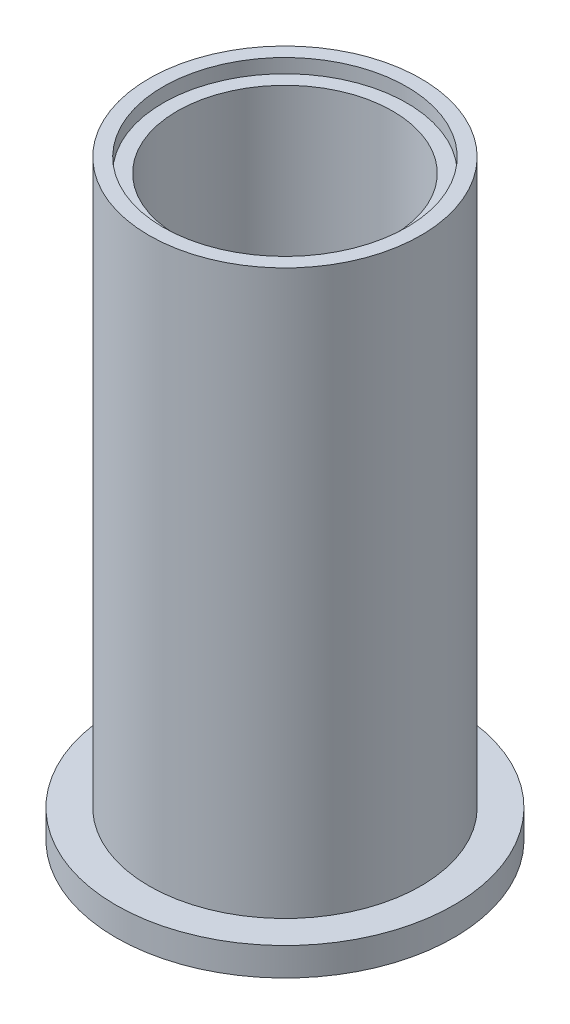
SolidWorks part; units mm, degrees
ref_plane "Front Plane" through (0, 0, 0) normal (0, 0, 1) x (1, 0, 0)
ref_plane "Top Plane" through (0, 0, 0) normal (0, 1, 0) x (1, 0, 0)
ref_plane "Right Plane" through (0, 0, 0) normal (1, 0, 0) x (0, 0, -1)
sketch "Sketch1" plane through (0, 0, 0) normal (0, 1, 0) x (1, 0, 0)
  circle A0 centre (0, 0) radius 60
  dimension "D1" = 120
extrude "Boss-Extrude1" add sketch "Sketch1" along normal blind 10
sketch "Sketch2" plane through (0, 10, 0) normal (0, 1, 0) x (1, 0, 0)
  circle A0 centre (0, 0) radius 38.25
  circle A1 centre (0, 0) radius 48.25
  dimension "D1" = 10
  dimension "D2" = 96.5
extrude "Boss-Extrude2" add sketch "Sketch2" along normal blind 200
sketch "Sketch3" plane through (0, 210, 0) normal (0, 1, 0) x (1, 0, 0)
  circle A0 centre (0, 0) radius 43.25
  circle A1 centre (0, 0) radius 38.25 construction
  dimension "D1" = 5
extrude "Cut-Extrude1" cut sketch "Sketch3" against normal blind 5
